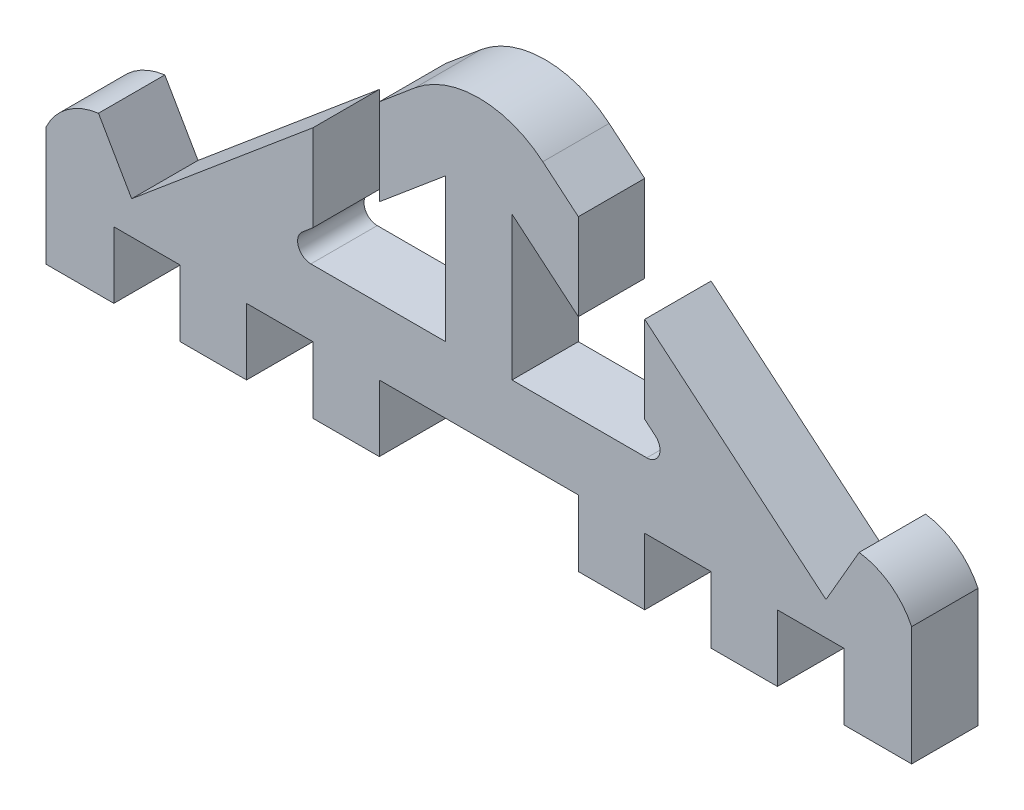
SolidWorks part; units mm, degrees
ref_plane "Front Plane" through (0, 0, 0) normal (0, 0, 1) x (1, 0, 0)
ref_plane "Top Plane" through (0, 0, 0) normal (0, 1, 0) x (1, 0, 0)
ref_plane "Right Plane" through (0, 0, 0) normal (1, 0, 0) x (0, 0, -1)
sketch "Sketch1" plane through (0, 0, 0) normal (0, 0, 1) x (1, 0, 0)
  line L0 (-3.175, 0) -> (3.175, 0) construction
  line L1 (0, 11.2776) -> (0, 14.4526) construction
  line L2 (0, 5.3239) -> (0, 29.3349) construction
  line L3 (-16.8861, 10.7417) -> (-15.875, 11.5902)
  line L4 (16.8861, 10.7417) -> (15.875, 11.5902)
  line L5 (-33.2218, 5.3239) -> (-25.4, 5.3239) construction
  line L6 (-9.525, 2.1489) -> (-9.525, -4.2011)
  line L7 (16.0698, 8.4989) -> (3.175, 8.4989)
  line L8 (-29.1401, 0.4595) -> (-2.0409, 23.1984) construction
  line L9 (41.4185, -4.2011) -> (41.4185, 7.178)
  line L10 (-36.3968, 10.8231) -> (-33.2218, 5.3239)
  line L11 (-41.4185, -4.2011) -> (-41.4185, 7.178)
  line L12 (-15.875, 8.4989) -> (-22.225, 8.4989) construction
  line L13 (-15.875, 11.5902) -> (-15.875, 19.8795)
  line L14 (29.1401, 0.4595) -> (2.0409, 23.1984) construction
  line L15 (-9.525, 25.2078) -> (-6.1226, 28.0628)
  line L16 (-33.2218, 5.3239) -> (-6.1226, 28.0628) construction
  line L17 (36.3968, 10.8231) -> (33.2218, 5.3239)
  line L18 (-9.525, 16.9185) -> (-3.175, 22.2467)
  line L19 (-9.525, 25.2078) -> (-9.525, 16.9185)
  line L20 (15.875, 11.5902) -> (15.875, 19.8795)
  line L21 (-34.925, -4.2011) -> (-41.4185, -4.2011)
  line L22 (9.525, 25.2078) -> (9.525, 16.9185)
  line L23 (-15.875, -4.2011) -> (-15.875, 2.1489)
  line L24 (-22.225, 2.1489) -> (-22.225, -4.2011)
  line L25 (-22.225, -4.2011) -> (-28.575, -4.2011)
  line L26 (41.4185, -4.2011) -> (34.925, -4.2011)
  line L27 (-28.575, -4.2011) -> (-28.575, 2.1489)
  line L28 (-34.925, 2.1489) -> (-34.925, -4.2011)
  line L29 (-9.525, -4.2011) -> (-15.875, -4.2011)
  line L30 (9.525, 2.1489) -> (9.525, -4.2011)
  line L31 (-15.875, 2.1489) -> (-22.225, 2.1489)
  line L32 (-28.575, 2.1489) -> (-34.925, 2.1489)
  line L33 (15.875, -4.2011) -> (9.525, -4.2011)
  line L34 (15.875, -4.2011) -> (15.875, 2.1489)
  line L35 (22.225, 2.1489) -> (22.225, -4.2011)
  line L36 (28.575, -4.2011) -> (22.225, -4.2011)
  line L37 (28.575, -4.2011) -> (28.575, 2.1489)
  line L38 (34.925, 2.1489) -> (34.925, -4.2011)
  line L39 (-33.2218, 5.3239) -> (-15.875, 19.8795)
  line L40 (15.875, 2.1489) -> (22.225, 2.1489)
  line L41 (9.525, 25.2078) -> (6.1226, 28.0628)
  line L42 (28.575, 2.1489) -> (34.925, 2.1489)
  line L43 (33.2218, 5.3239) -> (15.875, 19.8795)
  line L44 (33.2218, 5.3239) -> (6.1226, 28.0628) construction
  line L45 (9.525, 16.9185) -> (3.175, 22.2467)
  line L46 (3.175, 8.4989) -> (3.175, 22.2467)
  line L47 (-3.175, 8.4989) -> (-3.175, 22.2467)
  line L48 (9.525, 2.1489) -> (-9.525, 2.1489)
  line L49 (3.175, 5.3239) -> (3.175, 29.3349) construction
  line L50 (-3.175, 8.4989) -> (-16.0698, 8.4989)
  line L51 (-41.275, -3.175) -> (-41.275, 0) [skipped]
  line L52 (-3.175, 5.3239) -> (-3.175, 29.3349) construction
  arc A0 (-6.1226, 28.0628) -> (6.1226, 28.0628) centre (0, 20.7662) cw
  arc A2 (16.0698, 8.4989) -> (16.8861, 10.7417) centre (16.0698, 9.7689) ccw
  arc A3 (-16.8861, 10.7417) -> (-16.0698, 8.4989) centre (-16.0698, 9.7689) ccw
  arc A4 (-2.0409, 23.1984) -> (2.0409, 23.1984) centre (0, 20.7662) cw construction
  arc A6 (-36.3968, 10.8231) -> (-41.4185, 7.178) centre (-35.5558, 4.3828) ccw
  arc A7 (36.3968, 10.8231) -> (41.4185, 7.178) centre (35.5558, 4.3828) cw
  point P3 (0, 6.35)
  point P4 (0, 20.0838)
  point P5 (0, 20.0838)
  point P6 (0, 14.4526)
  point P8 (0, 33.2002)
  point P26 (9.525, 9.2085)
  point P32 (0, 5.3239)
  point P34 (0, 20.0838)
  point P43 (0, 3.175)
  point P50 (0, 6.35)
  point P53 (0, 16.9088)
  point P54 (9.525, 5.3239)
  point P58 (-9.525, 5.3239)
  point P61 (0, 3.175)
  point P67 (-9.525, 9.2085)
  point P85 (0, 6.35)
  point P86 (0, 11.2776)
  dimension "D5" = 3.175
  dimension "D9" = 80
  dimension "D10" = 9.525
  dimension "D6" = 6.35
  dimension "D4" = 6.35
  dimension "D2" = 6.4935
  dimension "D12" = 1.27
  dimension "D3" = 3.175
  dimension "D7" = 40
  dimension "D14" = 3.175
  dimension "D8" = 6.4935
  dimension "D11" = 6.35
  dimension "D13" = 3
extrude "Boss-Extrude1" add sketch "Sketch1" along normal blind 6.35
